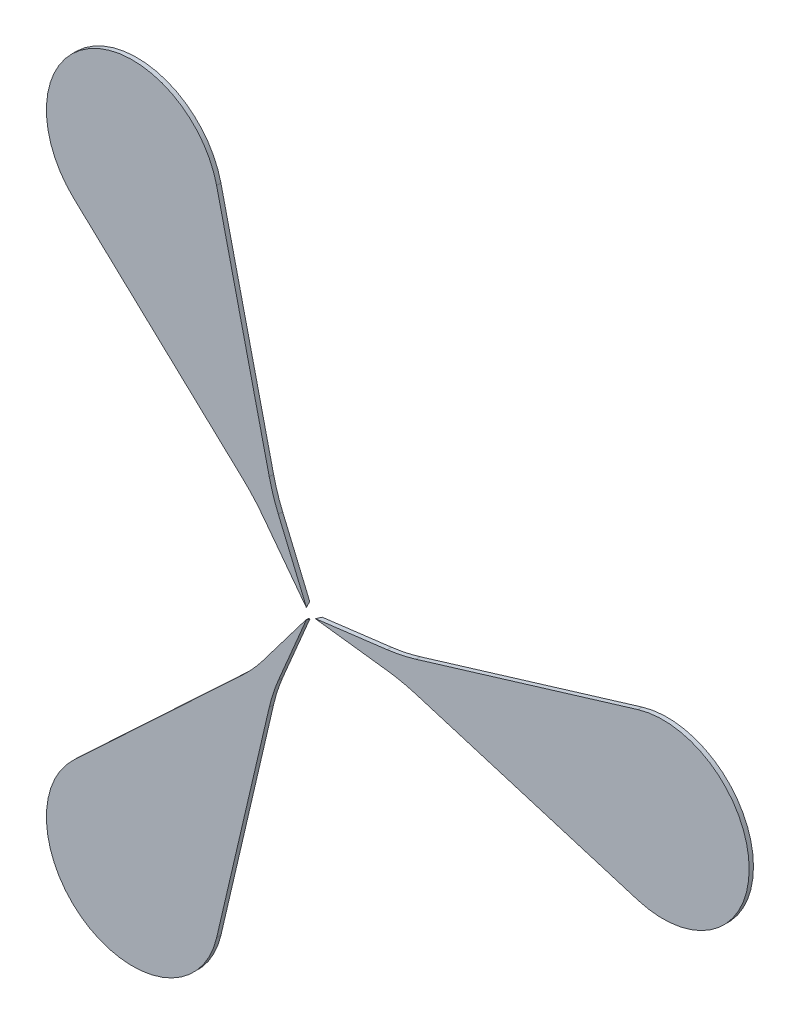
SolidWorks part; units mm, degrees
ref_plane "前基準面" through (0, 0, 0) normal (0, 0, 1) x (1, 0, 0)
ref_plane "上基準面" through (0, 0, 0) normal (0, 1, 0) x (1, 0, 0)
ref_plane "右基準面" through (0, 0, 0) normal (1, 0, 0) x (0, 0, -1)
sketch "草圖1" plane through (0, 0, 0) normal (0, 0, 1) x (1, 0, 0)
  line L0 (0.3574, 0.005) -> (20.1903, 2.4807) construction
  line L5 (0.3574, -0.005) -> (20.1903, -2.4807) construction
  line L6 (0.3574, 0.005) -> (4.5094, 0.5233)
  line L7 (0.3574, -0.005) -> (4.5094, -0.5233)
  line L8 (6.1751, 0.8773) -> (19.0478, 4.7845)
  line L9 (6.1751, -0.8773) -> (19.0478, -4.7845)
  line L10 (-0.183, -0.307) -> (-2.7079, -3.6436)
  line L11 (-3.8473, -4.9091) -> (-13.6674, -14.1037)
  line L12 (-2.3278, -5.7864) -> (-5.3804, -18.8881)
  line L13 (-0.1744, -0.312) -> (-1.8015, -4.1669)
  line L14 (-0.1744, 0.312) -> (-1.8015, 4.1669)
  line L15 (-2.3278, 5.7864) -> (-5.3804, 18.8881)
  line L16 (-3.8473, 4.9091) -> (-13.6674, 14.1037)
  line L17 (-0.183, 0.307) -> (-2.7079, 3.6436)
  circle A0 centre (0, 0) radius 0.353 construction
  arc A1 (0.3574, 0.005) -> (0.3574, -0.005) centre (0.358, 0) ccw
  circle A2 centre (20.5, 0) radius 2.5 construction
  arc A3 (19.0478, -4.7845) -> (19.0478, 4.7845) centre (20.5, 0) ccw
  arc A4 (4.5094, -0.5233) -> (6.1751, -0.8773) centre (3.2707, -10.4463) cw
  arc A5 (4.5094, 0.5233) -> (6.1751, 0.8773) centre (3.2707, 10.4463) ccw
  arc A6 (-0.1744, -0.312) -> (-0.183, -0.307) centre (-0.179, -0.31) ccw
  arc A7 (-2.7079, -3.6436) -> (-3.8473, -4.9091) centre (-10.6821, 2.3906) cw
  arc A8 (-13.6674, -14.1037) -> (-5.3804, -18.8881) centre (-10.25, -17.7535) ccw
  arc A9 (-1.8015, -4.1669) -> (-2.3278, -5.7864) centre (7.4114, -8.0556) ccw
  arc A10 (-0.183, 0.307) -> (-0.1744, 0.312) centre (-0.179, 0.31) ccw
  arc A11 (-1.8015, 4.1669) -> (-2.3278, 5.7864) centre (7.4114, 8.0556) cw
  arc A12 (-5.3804, 18.8881) -> (-13.6674, 14.1037) centre (-10.25, 17.7535) ccw
  arc A13 (-2.7079, 3.6436) -> (-3.8473, 4.9091) centre (-10.6821, -2.3906) ccw
  point P18 (5.3574, -0.6291)
  point P21 (5.3574, 0.6291)
  point P46 (0, 0)
  dimension "D1" = 0.706
  dimension "D2" = 0.01
  dimension "D3" = 5
  dimension "D4" = 20.5
  dimension "D6" = 10
  dimension "D7" = 10
  dimension "D8" = 3
  dimension "D5" = 5
extrude "填料-伸長2" add sketch "草圖1" along normal blind 0.25
sketch "草圖2" plane through (0, 0, 0) normal (0, 1, 0) x (1, 0, 0)
  line L0 (0, 0.3856) -> (0, -0.5968) construction
  line L1 (0.353, -0.25) -> (0.4973, 0)
  line L2 (4.5094, 0) -> (0.3574, 0) construction
  line L3 (0.4973, 0) -> (0.353, 0)
  line L4 (0.353, 0) -> (0.353, -0.25)
  dimension "D1" = 30
revolve "除料-旋轉1" cut sketch "草圖2" angle 360 about L0
